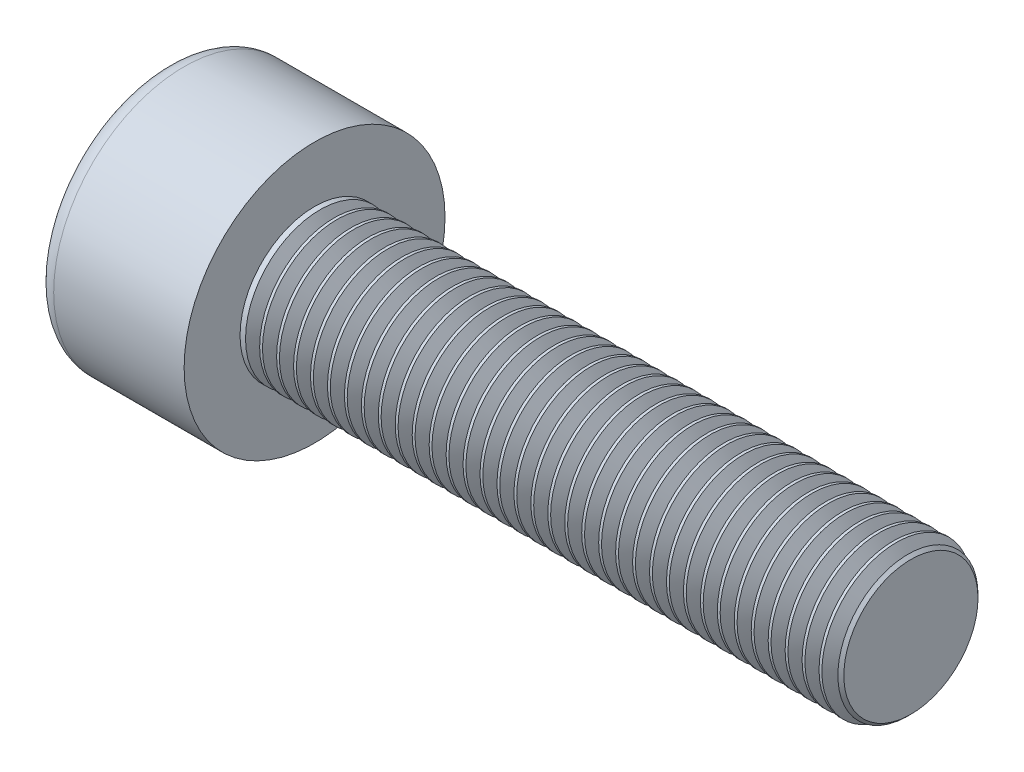
SolidWorks part; units mm, degrees
ref_plane "Front" through (0, 0, 0) normal (0, 0, 1) x (1, 0, 0)
ref_plane "Top" through (0, 0, 0) normal (0, 1, 0) x (1, 0, 0)
ref_plane "Right" through (0, 0, 0) normal (1, 0, 0) x (0, 0, -1)
sketch "Sketch1" plane through (0, 0, 0) normal (1, 0, 0) x (0, 0, -1)
  circle A0 centre (0, 0) radius 3.5
  dimension "dk" = 7
extrude "BaseHead" add sketch "Sketch1" along normal blind 4
sketch "Sketch2" plane through (4, 0, 0) normal (1, 0, 0) x (0, 0, -1)
  circle A0 centre (0, 0) radius 2
  dimension "d" = 4
extrude "BaseBody" add sketch "Sketch2" along normal blind 16
cosmetic thread "ThreadCosmetic1" [suppressed] parameters "b"=16, "D2"=3.242
sketch "Sketch3" plane through (0, 0, 0) normal (1, 0, 0) x (0, 0, -1)
  line L1 (1.7321, 0) -> (0.866, 1.5)
  line L2 (0.866, 1.5) -> (-0.866, 1.5)
  line L3 (-0.866, 1.5) -> (-1.7321, 0)
  line L4 (-1.7321, 0) -> (-0.866, -1.5)
  line L5 (-0.866, -1.5) -> (0.866, -1.5)
  line L6 (0.866, -1.5) -> (1.7321, 0)
  circle A0 centre (0, 0) radius 1.5 construction
  dimension "s" = 3
  dimension "e" = 3.4641
extrude "HexagonSocket" cut sketch "Sketch3" along normal blind 2
sketch "Sketch4" plane through (-4.1961, 0.75, 0) normal (0, 0, 1) x (-1, 0, 0)
  line L0 (-6.1961, 2.25) -> (-7.0622, 0.75)
  line L2 (-7.0622, 0.75) -> (-6.1961, 0.75)
  line L3 (-6.1961, 0.75) -> (-6.1961, 2.25)
  line L4 (-5.0351, 0.75) -> (0.839, 0.75) construction
  line L5 (-24.1961, 0.75) -> (-8.1961, 0.75) construction
  line L6 (-8.1961, 0.75) -> (-4.1961, 0.75) construction
  dimension "m" = 60
revolve "Cut-Revolve1" cut sketch "Sketch4" angle 360 about L4
fillet "HeadFillet" [suppressed] radius 0.2
fillet "TopFillet" radius 0.5 1 edges at (0, 0, -3.5)
chamfer "Chamfer1" distance 0.2 angle 45 1 edges at (20, 0, -2)
sketch "Sketch5" plane through (0, 0, 0) normal (0, 0, 1) x (1, 0, 0)
  line L0 (19.8, 1.6718) -> (19.9895, 2)
  line L1 (19.9895, 2) -> (19.9895, 2.379)
  line L2 (19.9895, 2.379) -> (19.6105, 2.379)
  line L3 (19.6105, 2.379) -> (19.6105, 2)
  line L4 (19.6105, 2) -> (19.8, 1.6718)
  line L5 (0, 0) -> (7.8886, 0) construction
  line L6 (19.8, -2) -> (19.8, 2) construction
  dimension "D1" = 4
  dimension "D2" = 0.379
revolve "Cut-Revolve10" cut sketch "Sketch5" angle 360 about L5
pattern_linear "LPattern10" count 35 spacing 0.4548 along (-1, 0, 0) of "Cut-Revolve10"
equation "\"r1@TopFillet\" = \"d@Sketch2\" / 8"
equation "\"D1@Chamfer1\" = \"r@HeadFillet\""
equation "\"D1@Sketch5\" = \"d@Sketch2\""
equation "\"D2@Sketch5\" =  ( \"d@Sketch2\" - \"D2@ThreadCosmetic1\" )  / 2"
equation "\"D3@LPattern10\" = \"D2@Sketch5\" * 1.2"
equation "\"D1@LPattern10\" = \"b@ThreadCosmetic1\" / \"D3@LPattern10\""
